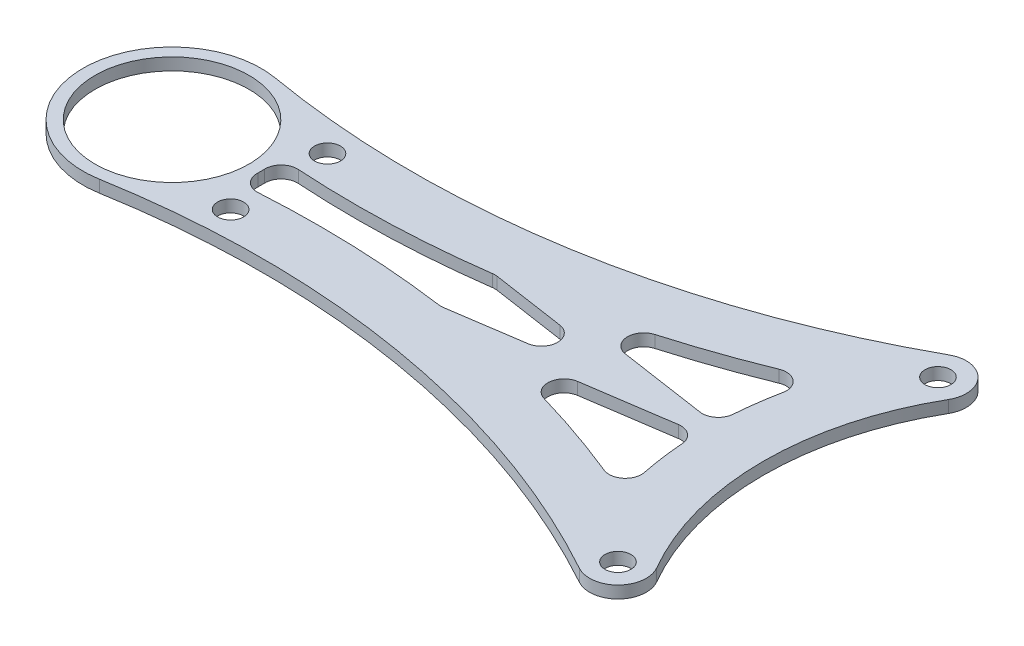
SolidWorks part; units mm, degrees
material "Thornel Mat VMA"
ref_plane "Front Plane" through (0, 0, 0) normal (0, 0, 1) x (1, 0, 0)
ref_plane "Top Plane" through (0, 0, 0) normal (0, 1, 0) x (1, 0, 0)
ref_plane "Right Plane" through (0, 0, 0) normal (1, 0, 0) x (0, 0, -1)
sketch "Sketch1" plane through (0, 0, 0) normal (0, 1, 0) x (1, 0, 0)
  line L0 (0, 0) -> (-43, 0) construction
  line L1 (0, 0) -> (-37.2391, 21.5) construction
  line L2 (0, 0) -> (-37.2391, -21.5) construction
  arc A0 (-37.2391, 21.5) -> (-37.2391, -21.5) centre (0, 0) ccw
  arc A1 (-107.1267, 10.8393) -> (-107.1267, -10.8393) centre (-109, 0) ccw
  arc A2 (-31.1769, 18) -> (-31.1769, -18) centre (0, 0) ccw
  circle A3 centre (-34.208, 19.75) radius 3.5
  circle A4 centre (-34.208, -19.75) radius 3.5
  arc A5 (-107.1267, 10.8393) -> (-35.8991, 22.8144) centre (-88.564, 118.2471) ccw
  arc A6 (-107.1267, -10.8393) -> (-35.8991, -22.8144) centre (-88.564, -118.2471) cw
  dimension "D2" = 22
  dimension "D3" = 86
  dimension "D4" = 7
  dimension "D7" = 109
  dimension "D1" = 109
  dimension "D5" = 30
  dimension "D6" = 30
  dimension "D8" = 0
extrude "Boss-Extrude1" add sketch "Sketch1" along normal mid plane 1.5 contours A1 A6 A4 A0 A3 A5 | A4 A2 A3 A0 | A4 | A3
hole_wizard "Ø3.2 (3.2) Diameter Hole1" positions "Sketch5" profile "Sketch4" hole size "Ø3.2" standard "ANSI Metric"
sketch "Sketch5" plane through (0, 0.75, 0) normal (0, 1, 0) x (1, 0, 0)
  circle A0 centre (-109, 0) radius 11
  circle A1 centre (-95.7903, 5.9794) radius 3.5
  circle A2 centre (-95.7903, -5.9794) radius 3.5
  arc A3 (-35.8991, -22.8144) -> (-107.1267, -10.8393) centre (-88.564, -118.2471) ccw construction
  arc A4 (-107.1267, 10.8393) -> (-35.8991, 22.8144) centre (-88.564, 118.2471) ccw construction
  point P0 (-34.208, 19.75)
  point P3 (-34.208, -19.75)
  point P11 (-95.7903, 5.9794)
  point P13 (-95.7903, -5.9794)
  dimension "D1" = 7
sketch "Sketch4" plane through (-34.208, 0.75, -19.75) normal (1, 0, 0) x (0, 0, 1)
  line L0 (0, 0) -> (0, 10.9614)
  line L1 (0, 10.9614) -> (1.6, 10)
  line L2 (1.6, 10) -> (1.6, 0)
  line L5 (1.6, 0) -> (0, 0)
  line L10 (0, 10.9614) -> (-1.6, 10) construction
  line L11 (0, -6.35) -> (0, 107.95) construction
  dimension "Hole Dia." = 3.2
  dimension "Hole Depth" = 10
  dimension "Drill Angle" = 118
sketch "Sketch6" plane through (0, 0.75, 0) normal (0, 1, 0) x (1, 0, 0)
  line L0 (-43, 0) -> (-69.1391, -3.8851)
  line L1 (-43, 0) -> (-69.1391, 3.8851)
  line L2 (-42.853, 0.9891) -> (-68.9921, 4.8742)
  line L3 (-43.147, -0.9891) -> (-72.4693, 3.369)
  line L4 (-43.147, 0.9891) -> (-72.4693, -3.369)
  line L5 (-42.853, -0.9891) -> (-68.9921, -4.8742)
  line L6 (-43.147, -0.9891) -> (-69.2861, 2.8959) construction
  line L7 (-43.147, 0.9891) -> (-69.2861, -2.8959) construction
  arc A2 (-108.3188, 3.9416) -> (-32.5169, 16.6856) centre (-88.564, 118.2471) ccw
  arc A3 (-98.3261, 2.6586) -> (-41.184, 12.3644) centre (-88.564, 118.2471) ccw
  arc A5 (-32.5169, -16.6856) -> (-108.3188, -3.9416) centre (-88.564, -118.2471) ccw
  arc A6 (-41.184, -12.3644) -> (-98.3261, -2.6586) centre (-88.564, -118.2471) ccw
  arc A7 (-98.3261, -2.6586) -> (-98.3261, 2.6586) centre (-109, 0) ccw
  arc A8 (-37.2391, 21.5) -> (-37.2391, -21.5) centre (0, 0) ccw
  arc A9 (-41.184, 12.3644) -> (-41.184, -12.3644) centre (0, 0) ccw
  dimension "D1" = 7
  dimension "D2" = 7
  dimension "D3" = 7
  dimension "D4" = 1
  dimension "D5" = 1
  dimension "D6" = 1
  dimension "D7" = 1
extrude "Cut-Extrude1" cut sketch "Sketch6" against normal through all contours A7 A6 L4 L3 A3 | A9 A3 L2 | A9 L5 A6
fillet "Fillet1" radius 2 11 edges at (-41.184, 0, 12.3644) (-42.9882, 0, -1.0092) (-41.184, 0, -12.3644) (-42.9882, 0, 1.0092) (-66.0961, 0, -4.4438) (-66.0961, 0, 4.4438) (-49.802, 0, 0) (-72.4693, 0, 3.369) (-72.4693, 0, -3.369) (-98.3261, 0, 2.6586) (-98.3261, 0, -2.6586)
sketch "Sketch7" plane through (0, 0.75, 0) normal (0, 1, 0) x (1, 0, 0)
  circle A0 centre (-109, 0) radius 9.5
  dimension "D1" = 19
extrude "Cut-Extrude2" cut sketch "Sketch7" against normal through all
